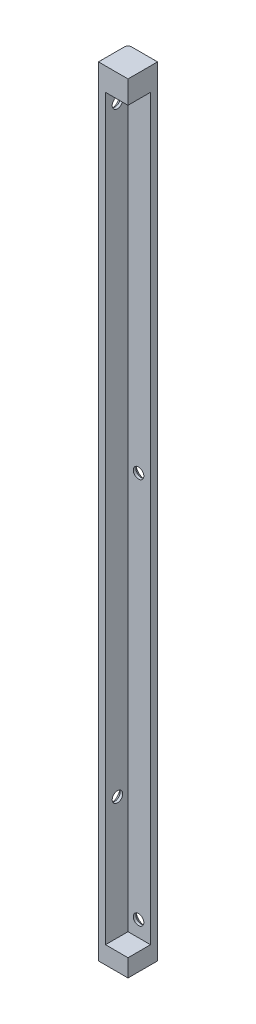
SolidWorks part; units mm, degrees
material "Aluminum"
ref_plane "Front Plane" through (0, 0, 0) normal (0, 0, 1) x (1, 0, 0)
ref_plane "Top Plane" through (0, 0, 0) normal (0, 1, 0) x (1, 0, 0)
ref_plane "Right Plane" through (0, 0, 0) normal (1, 0, 0) x (0, 0, -1)
sketch "Sketch1" plane through (0, 0, 0) normal (0, 1, 0) x (1, 0, 0)
  line L0 (0, 0) -> (0, 9)
  line L1 (0, 9) -> (9, 9)
  line L2 (2, 0) -> (2, 7)
  line L3 (2, 7) -> (9, 7)
  line L4 (9, 9) -> (9, 7)
  line L5 (0, 0) -> (2, 0)
  dimension "D1" = 9
  dimension "D2" = 9
  dimension "D3" = 2
extrude "Boss-Extrude1" add sketch "Sketch1" along normal blind 221.5
hole_wizard "CSK for M3 Countersunk Flat Head Screw1" positions "Sketch5" profile "Sketch4" countersink size "M3" standard "ISO" end condition through all
sketch "Sketch5" plane through (0, 0, 0) normal (-1, 0, 0) x (0, 0, 1)
  line L6 (-9, 221.5) -> (-9, 0) construction
  line L10 (-10.8951, 111.1396) -> (-76.4926, 111.1396) construction
  point P32 (-4, 211.25)
  point P40 (-4, 40.25)
  dimension "D1" = 100.1104
  dimension "D2" = 5
sketch "Sketch4" plane through (0, 211.25, -4) normal (0, 1, 0) x (0, 0, 1)
  line L0 (0, 0) -> (0, 9)
  line L1 (0, 9) -> (1.5, 9)
  line L2 (1.5, 9) -> (1.5, 1.25)
  line L3 (1.5, 1.25) -> (2.75, 0)
  line L5 (2.75, 0) -> (0, 0)
  line L6 (-1.5, 1.25) -> (-2.75, 0) construction
  line L11 (0, -6.35) -> (0, 107.95) construction
  dimension "Thru Hole Dia." = 3
  dimension "Thru Hole Depth" = 9
  dimension "Near C'Sink Dia." = 5.5
  dimension "Near C'Sink Angle" = 90
hole_wizard "CSK for M3 Countersunk Flat Head Screw4" positions "Sketch11" profile "Sketch10" countersink size "M3" standard "ISO" end condition through all
sketch "Sketch11" plane through (0, 0, -9) normal (0, 0, -1) x (-1, 0, 0)
  line L4 (0, 221.5) -> (0, 0) construction
  line L5 (0, 109.7032) -> (-46.6843, 109.7032) construction
  point P2 (-5, 120)
  point P23 (-5, 10)
  dimension "D1" = 10.2968
  dimension "D3" = 5
sketch "Sketch10" plane through (5, 120, -9) normal (1, 0, 0) x (0, 1, 0)
  line L0 (0, 0) -> (0, 9)
  line L1 (0, 9) -> (1.5, 9)
  line L2 (1.5, 9) -> (1.5, 1.25)
  line L3 (1.5, 1.25) -> (2.75, 0)
  line L5 (2.75, 0) -> (0, 0)
  line L6 (-1.5, 1.25) -> (-2.75, 0) construction
  line L11 (0, -6.35) -> (0, 107.95) construction
  dimension "Thru Hole Dia." = 3
  dimension "Thru Hole Depth" = 9
  dimension "Near C'Sink Dia." = 5.5
  dimension "Near C'Sink Angle" = 90
sketch "Sketch12" plane through (0, 0, 0) normal (0, -1, 0) x (1, 0, 0)
  line L0 (2, -7) -> (9, -7) construction
  line L1 (1, -7) -> (9, -7)
  line L2 (1, -7) -> (1, 0)
  line L3 (1, 0) -> (9, 0)
  line L4 (9, -7) -> (9, 0)
  line L5 (9, -7) -> (9, -9) construction
extrude "Boss-Extrude2" add sketch "Sketch12" against normal blind 5.5
sketch "Sketch13" plane through (0, 221.5, 0) normal (0, 1, 0) x (1, 0, 0)
  line L0 (0, 8) -> (1, 9)
  line L1 (0, 9) -> (0, 0) construction
  line L2 (9, 9) -> (0, 9) construction
  line L3 (0, 8) -> (0, 9)
  line L4 (0, 9) -> (1, 9)
  dimension "D1" = 1
  dimension "D2" = 1
extrude "Cut-Extrude1" cut sketch "Sketch13" against normal blind 359
sketch "Sketch14" plane through (0, 0, 0) normal (0, -1, 0) x (1, 0, 0)
  line L0 (0, 0) -> (9, 0)
  line L1 (9, 0) -> (9, -9)
  line L2 (9, -9) -> (1, -9)
  line L3 (1, -9) -> (0, -8)
  line L4 (0, -8) -> (0, 0)
extrude "Boss-Extrude3" add sketch "Sketch14" along normal blind 3
sketch "Sketch18" plane through (0, 221.5, 0) normal (0, 1, 0) x (1, 0, 0)
  line L1 (0, 0) -> (9, 0)
  line L2 (0, 0) -> (0, 8)
  line L3 (1, 9) -> (9, 9)
  line L4 (9, 0) -> (9, 9)
  line L5 (1, 9) -> (0, 8)
  dimension "D1" = 9
  dimension "D2" = 9
extrude "Boss-Extrude4" add sketch "Sketch18" along normal blind 2.5 and the other way blind 6
sketch "Sketch19" plane through (0, 0, -9) normal (0, 0, -1) x (-1, 0, 0)
  line L0 (-1, -3) -> (-9, -3) construction
  line L1 (-9, -3) -> (-8.4, -3)
  line L2 (-9, -3) -> (-9, 224)
  line L3 (-9, 224) -> (-8.4, 224)
  line L4 (-8.4, -3) -> (-8.4, 224)
  line L5 (-9, 224) -> (-9, -3) construction
  line L6 (-9, 224) -> (-1, 224) construction
  dimension "D1" = 0.6
extrude "Cut-Extrude2" cut sketch "Sketch19" against normal blind 10
sketch "Sketch20" plane through (0, 0, 0) normal (0, 0, 1) x (1, 0, 0)
  line L1 (8.4, 224) -> (-5.489, 224)
  line L2 (8.4, 224) -> (8.4, 222)
  line L3 (8.4, 222) -> (-5.489, 222)
  line L4 (-5.489, 224) -> (-5.489, 222)
  dimension "D1" = 2
extrude "Cut-Extrude3" cut sketch "Sketch20" against normal blind 10
sketch "Sketch21" plane through (0, 0, 0) normal (-1, 0, 0) x (0, 0, 1)
  line L0 (0, 222) -> (-8, 222) construction
  line L1 (0, 222) -> (-0.6, 222)
  line L2 (0, 222) -> (0, -3)
  line L3 (0, -3) -> (-0.6, -3)
  line L4 (-0.6, 222) -> (-0.6, -3)
  line L5 (0, -3) -> (-8, -3) construction
  line L6 (0, 222) -> (0, -3) construction
  dimension "D1" = 0.6
extrude "Cut-Extrude4" cut sketch "Sketch21" against normal blind 10
sketch "Sketch22" plane through (8.4, 0, 0) normal (1, 0, 0) x (0, 0, -1)
  line L0 (0.6, 5.5) -> (0.6, -3) construction
  line L1 (0.6, -3) -> (9, -3)
  line L2 (0.6, -3) -> (0.6, 2.5)
  line L3 (0.6, 2.5) -> (9, 2.5)
  line L4 (9, -3) -> (9, 2.5)
  line L5 (9, -3) -> (9, 222) construction
  dimension "D1" = 5.5
extrude "Cut-Extrude5" cut sketch "Sketch22" against normal blind 10
sketch "Sketch23" plane through (0, 2.5, 0) normal (0, -1, 0) x (1, 0, 0)
  line L0 (1, -9) -> (8.4, -9)
  line L1 (8.4, -9) -> (8.4, -0.6)
  line L2 (8.4, -0.6) -> (0, -0.6)
  line L3 (0, -0.6) -> (0, -8)
  line L4 (0, -8) -> (1, -9)
extrude "Boss-Extrude5" add sketch "Sketch23" along normal blind 2
sketch "Sketch24" plane through (0, 222, 0) normal (0, 1, 0) x (1, 0, 0)
  line L0 (0, 8) -> (1, 9)
  line L1 (1, 9) -> (0, 9)
  line L2 (0, 9) -> (0, 8)
extrude "Boss-Extrude6" add sketch "Sketch24" against normal blind 221.5
fillet "Fillet1" radius 1 1 edges at (0, 111.25, -9)
